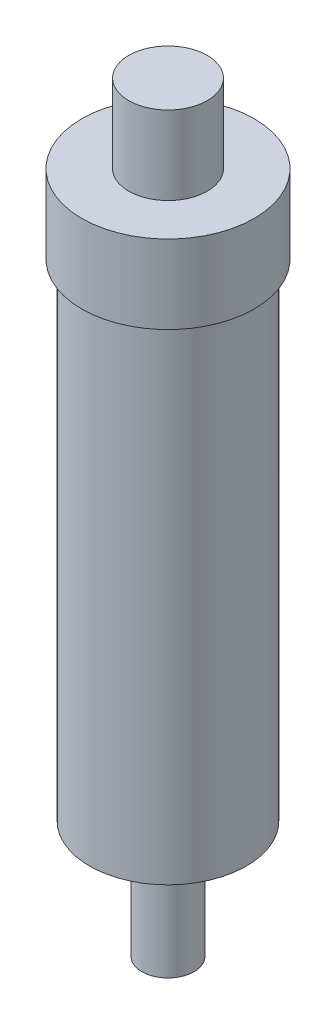
SolidWorks part; units mm, degrees
ref_plane "Front Plane" through (0, 0, 0) normal (0, 0, 1) x (1, 0, 0)
ref_plane "Top Plane" through (0, 0, 0) normal (0, 1, 0) x (1, 0, 0)
ref_plane "Right Plane" through (0, 0, 0) normal (1, 0, 0) x (0, 0, -1)
sketch "Sketch1" plane through (0, 0, 0) normal (0, 0, 1) x (1, 0, 0)
  line L0 (12.7, 182.88) -> (27.94, 182.88)
  line L1 (8.4502, 0) -> (25.4, 0)
  line L2 (0, 0) -> (0, 182.88)
  line L4 (25.4, 0) -> (25.4, 157.48)
  line L5 (25.4, 157.48) -> (27.94, 157.48)
  line L7 (0, 0) -> (0, -38.1)
  line L8 (27.94, 157.48) -> (27.94, 182.88)
  line L9 (0, -38.1) -> (8.4502, -38.1)
  line L10 (8.4502, 0) -> (8.4502, -38.1)
  line L11 (0, 182.88) -> (0, 208.28)
  line L12 (0, 208.28) -> (12.7, 208.28)
  line L13 (12.7, 182.88) -> (12.7, 208.28)
  dimension "D1" = 157.48
  dimension "D2" = 25.4
  dimension "D3" = 25.4
  dimension "D4" = 2.54
  dimension "D5" = 38.1
  dimension "D6" = 8.4502
  dimension "D7" = 12.7
  dimension "D8" = 25.4
revolve "Revolve1" add sketch "Sketch1" angle 360 about L2
sketch "Sketch2" plane through (0, -38.1, 0) normal (0, -1, 0) x (1, 0, 0)
  circle A0 centre (0, 0) radius 1.905
  dimension "D1" = 3.81
extrude "Cut-Extrude1" cut sketch "Sketch2" against normal up to surface (38.1 mm away) up to face at (0, 0, -25.4)
